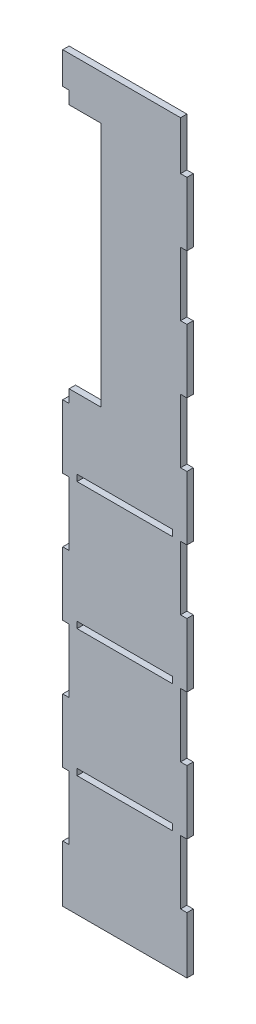
SolidWorks part; units mm, degrees
ref_plane "前视基准面" through (0, 0, 0) normal (0, 0, 1) x (1, 0, 0)
ref_plane "上视基准面" through (0, 0, 0) normal (0, 1, 0) x (1, 0, 0)
ref_plane "右视基准面" through (0, 0, 0) normal (1, 0, 0) x (0, 0, -1)
sketch "草图1" plane through (0, 0, 0) normal (0, 0, 1) x (1, 0, 0)
  line L42 (-8, -36.2215) -> (-10, -36.2215)
  line L43 (-10, -36.2215) -> (-10, -56.2215)
  line L44 (-10, -56.2215) -> (-8, -56.2215)
  line L45 (-8, -56.2215) -> (-8, -76.2215)
  line L46 (-8, -76.2215) -> (-10, -76.2215)
  line L47 (-10, -76.2215) -> (-10, -96.2215)
  line L48 (-10, -96.2215) -> (-8, -96.2215)
  line L49 (-8, -96.2215) -> (-8, -116.2215)
  line L52 (-8, -116.2215) -> (-10, -116.2215)
  line L53 (-10, -116.2215) -> (-10, -136.2215)
  line L54 (-10, -136.2215) -> (-8, -136.2215)
  line L56 (-8, -174) -> (27, -174)
  line L59 (2, -15.141) -> (2, 15.141)
  line L62 (29, -36.2215) -> (29, -56.2215)
  line L63 (29, -56.2215) -> (27, -56.2215)
  line L64 (27, -56.2215) -> (27, -76.2215)
  line L65 (27, -76.2215) -> (29, -76.2215)
  line L66 (29, -76.2215) -> (29, -96.2215)
  line L67 (29, -96.2215) -> (27, -96.2215)
  line L68 (27, -96.2215) -> (27, -116.2215)
  line L69 (29, -116.2215) -> (29, -136.2215)
  line L70 (29, -136.2215) -> (27, -136.2215)
  line L71 (27, -116.2215) -> (29, -116.2215)
  line L73 (27, -36.2215) -> (29, -36.2215)
  line L83 (-5.5, -94.2215) -> (-5.5, -96.2215)
  line L84 (-5.5, -96.2215) -> (24.5, -96.2215)
  line L85 (24.5, -96.2215) -> (24.5, -94.2215)
  line L86 (24.5, -94.2215) -> (-5.5, -94.2215)
  line L87 (-5.5, -134.2215) -> (-5.5, -136.2215)
  line L88 (-5.5, -136.2215) -> (24.5, -136.2215)
  line L89 (24.5, -136.2215) -> (24.5, -134.2215)
  line L90 (24.5, -134.2215) -> (-5.5, -134.2215)
  line L91 (-5.5, -56.2215) -> (-5.5, -54.2215)
  line L92 (-5.5, -56.2215) -> (24.5, -56.2215)
  line L93 (-5.5, -54.2215) -> (24.5, -54.2215)
  line L94 (24.5, -54.2215) -> (24.5, -56.2215)
  line L96 (-8, 49) -> (-10, 49)
  line L97 (-10, 49) -> (-10, 59)
  line L98 (-10, 59) -> (27, 59)
  line L99 (27, 59) -> (27, 49)
  line L104 (-8, -36.2215) -> (-8, -32.2215)
  line L108 (2, -31.2215) -> (2, -15.141)
  line L113 (2, 15.141) -> (2, 43.3425)
  line L114 (-8, -136.2215) -> (-8, -156.2215)
  line L115 (-8, -156.2215) -> (-10, -156.2215)
  line L116 (-10, -156.2215) -> (-10, -174)
  line L117 (-10, -174) -> (-8, -174)
  line L118 (27, -136.2215) -> (27, -156.2215)
  line L119 (27, -156.2215) -> (29, -156.2215)
  line L120 (29, -156.2215) -> (29, -174)
  line L121 (29, -174) -> (27, -174)
  line L122 (27, -36.2215) -> (27, -16.2215)
  line L123 (27, -16.2215) -> (29, -16.2215)
  line L124 (29, -16.2215) -> (29, 3.7785)
  line L125 (29, 3.7785) -> (27, 3.7785)
  line L126 (27, 3.7785) -> (27, 23.7785)
  line L127 (27, 23.7785) -> (29, 23.7785)
  line L128 (29, 23.7785) -> (29, 43.7785)
  line L129 (29, 43.7785) -> (27, 43.7785)
  line L130 (27, 43.7785) -> (27, 49)
  line L131 (-8, 49) -> (-8, 45)
  line L132 (-8, 45) -> (2, 45)
  line L133 (2, 45) -> (2, 43.3425)
  line L134 (-8, -32.2215) -> (2, -32.2215)
  line L135 (2, -32.2215) -> (2, -31.2215)
extrude "凸台-拉伸2" add sketch "草图1" along normal blind 2
